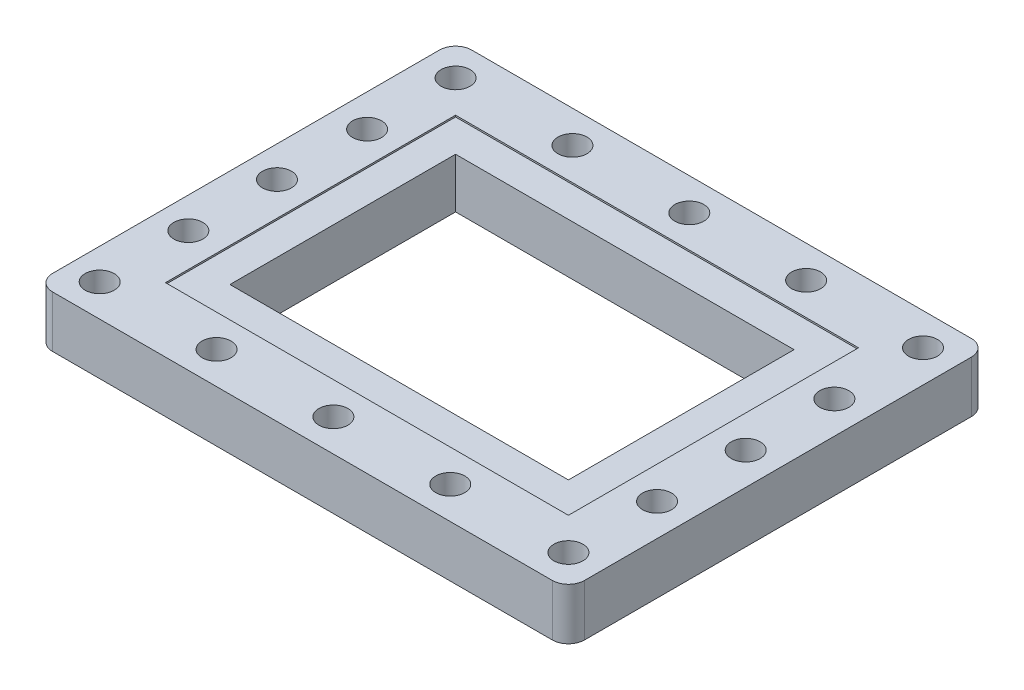
SolidWorks part; units mm, degrees
ref_plane "Front Plane" through (0, 0, 0) normal (0, 0, 1) x (1, 0, 0)
ref_plane "Top Plane" through (0, 0, 0) normal (0, 1, 0) x (1, 0, 0)
ref_plane "Right Plane" through (0, 0, 0) normal (1, 0, 0) x (0, 0, -1)
sketch "Sketch1" plane through (0, 0, 0) normal (0, 1, 0) x (1, 0, 0)
  line L1 (-14.684, 10.0891) -> (18.316, 10.0891)
  line L2 (-14.684, 10.0891) -> (-14.684, -15.9109)
  line L3 (-14.684, -15.9109) -> (18.316, -15.9109)
  line L4 (18.316, 10.0891) -> (18.316, -15.9109)
  dimension "D1" = 33
  dimension "D2" = 26
extrude "Boss-Extrude1" add sketch "Sketch1" along normal blind 3.1
sketch "Sketch2" plane through (0, 0, 15.9109) normal (0, 0, 1) x (1, 0, 0)
  line L0 (18.316, 3.1) -> (18.316, 0) construction
  line L1 (18.316, 2.1) -> (12.816, 2.1)
  line L2 (18.316, 2.1) -> (18.316, 1)
  line L3 (18.316, 1) -> (12.816, 1)
  line L4 (12.816, 2.1) -> (12.816, 1)
  line L5 (-14.684, 3.1) -> (18.316, 3.1) construction
  dimension "D1" = 5.5
  dimension "D2" = 1.1
  dimension "D3" = 1
extrude "Cut-Extrude1" [suppressed] cut sketch "Sketch2" against normal through all
sketch "Sketch3" plane through (0, 3.1, 0) normal (0, 1, 0) x (1, 0, 0)
  line L0 (-14.684, -15.9109) -> (18.316, -15.9109) construction
  line L1 (-14.684, 10.0891) -> (-10.684, 10.0891)
  line L2 (-14.684, 10.0891) -> (-14.684, -15.9109)
  line L3 (-14.684, -15.9109) -> (-10.684, -15.9109)
  line L4 (-10.684, 10.0891) -> (-10.684, -15.9109)
  line L5 (18.316, -15.9109) -> (18.316, 10.0891) construction
  line L6 (-10.684, 10.0891) -> (18.316, 10.0891)
  line L7 (-10.684, 10.0891) -> (-10.684, 6.0891)
  line L8 (-10.684, 6.0891) -> (18.316, 6.0891)
  line L9 (18.316, 10.0891) -> (18.316, 6.0891)
  line L11 (-10.684, -15.9109) -> (18.316, -15.9109)
  line L12 (-10.684, -15.9109) -> (-10.684, -11.9109)
  line L13 (-10.684, -11.9109) -> (18.316, -11.9109)
  line L14 (18.316, -15.9109) -> (18.316, -11.9109)
  line L15 (14.316, 6.0891) -> (18.316, 6.0891)
  line L16 (14.316, 6.0891) -> (14.316, -11.9109)
  line L17 (14.316, -11.9109) -> (18.316, -11.9109)
  line L18 (18.316, 6.0891) -> (18.316, -11.9109)
  line M7 (-14.684, 10.0891) -> (-14.684, -15.9109)
  line M8 (-14.684, -15.9109) -> (18.316, -15.9109)
  line M9 (18.316, -15.9109) -> (18.316, 10.0891)
  line M10 (18.316, 10.0891) -> (-14.684, 10.0891)
  dimension "D1" = 4
  dimension "D2" = 4
  dimension "D3" = 4
  dimension "D4" = 4
extrude "Boss-Extrude2" add sketch "Sketch3" along normal blind 0.1 contours L4 M10 M7 M8 | L4 L8 M9 M10 | L13 L4 M8 M9 | L16 L15 L18 L17
sketch "Sketch4" plane through (0, 0, 0) normal (0, -1, 0) x (1, 0, 0)
  line L0 (18.316, 15.9109) -> (18.316, -10.0891) construction
  line L1 (18.316, -10.0891) -> (-14.684, -10.0891) construction
  circle A0 centre (15.566, -5.3391) radius 0.5501
  circle A5 centre (15.566, 4.6609) radius 0.5501
  circle A6 centre (15.566, -0.3391) radius 0.5501
  circle A7 centre (10.7876, 6.1326) radius 0.5501
  dimension "D1" = 2.75
  dimension "D2" = 5
  dimension "D3" = 5
  dimension "D4" = 5
  dimension "D5" = 4.75
  dimension "D6" = 0
  dimension "D7" = 0
hole_wizard "Tap Drill for M2.5x0.45 Tap1" [suppressed] positions "Sketch5" profile "Sketch6" hole size "M2.5x0.45" standard "ANSI Metric"
sketch "Sketch5" plane through (0, 0, 0) normal (0, -1, 0) x (-1, 0, 0)
  point P0 (-3.066, 5.3391)
  point P3 (-3.066, 0.3391)
  point P6 (-3.066, -4.6609)
  point P9 (-3.0468, -9.6608)
sketch "Sketch6" plane through (3.066, 0, -5.3391) normal (1, 0, 0) x (0, 0, -1)
  line L0 (0, 0) -> (0, 1.675)
  line L1 (0, 1.675) -> (1.125, 0.999)
  line L2 (1.125, 0.999) -> (1.125, 0)
  line L5 (1.125, 0) -> (0, 0)
  line L10 (0, 1.675) -> (-1.125, 0.999) construction
  line L11 (0, -6.35) -> (0, 107.95) construction
  dimension "Hole Dia." = 2.25
  dimension "Hole Depth" = 0.999
  dimension "Drill Angle" = 118
sketch "Sketch7" plane through (0, 3.2, 0) normal (0, 1, 0) x (1, 0, 0)
  line L0 (-14.684, 10.0891) -> (-14.684, -15.9109) construction
  line L1 (18.316, -15.9109) -> (18.316, 10.0891) construction
  line L2 (18.316, 10.0891) -> (-14.684, 10.0891) construction
  circle A0 centre (-12.684, 8.0891) radius 0.882
  circle A1 centre (-12.7647, -13.9109) radius 0.882
  circle A2 centre (-12.6745, 2.5891) radius 0.882
  circle A3 centre (-12.7647, -2.9109) radius 0.882
  circle A4 centre (-12.7647, -8.4109) radius 0.882
  circle A5 centre (-5.434, 8.0891) radius 0.882
  circle A6 centre (1.816, 8.0891) radius 0.882
  circle A7 centre (1.7353, -13.9109) radius 0.882
  circle A9 centre (-5.5147, -13.9109) radius 0.882
  circle A10 centre (9.066, 8.0891) radius 0.882
  circle A11 centre (16.316, 8.0891) radius 0.882
  circle A12 centre (16.316, 2.5891) radius 0.882
  circle A13 centre (16.316, -2.9109) radius 0.882
  circle A14 centre (16.316, -8.4109) radius 0.882
  circle A15 centre (16.316, -13.9109) radius 0.882
  circle A16 centre (8.9853, -13.9109) radius 0.882
  dimension "D1" = 2
  dimension "D2" = 2
  dimension "D3" = 5.5
  dimension "D4" = 5.5
  dimension "D5" = 5.5
  dimension "D6" = 5.5
  dimension "D7" = 7.25
  dimension "D8" = 7.25
  dimension "D10" = 7.25
  dimension "D11" = 7.25
  dimension "D9" = 7.25
  dimension "D12" = 2
  dimension "D13" = 0
  dimension "D14" = 0
  dimension "D15" = 0
  dimension "D16" = 0
  dimension "D17" = 7.25
  dimension "D18" = 0
  dimension "D19" = 0
  dimension "D20" = 0
  dimension "D21" = 0
  dimension "D22" = 0
  dimension "D23" = 0
  dimension "D24" = 0
hole_wizard "Tap Drill for M2x0.4 Tap2" positions "Sketch8" profile "Sketch10" hole size "M2x0.4" standard "ANSI Metric" end condition through all
sketch "Sketch8" plane through (0, 3.2, 0) normal (0, 1, 0) x (1, 0, 0)
  point P0 (-12.684, 8.0891)
  point P4 (-12.6745, 2.5891)
  point P7 (-12.7647, -2.9109)
  point P10 (-12.7647, -8.4109)
  point P13 (-12.7647, -13.9109)
  point P16 (-5.434, 8.0891)
  point P19 (1.816, 8.0891)
  point P28 (1.7353, -13.9109)
  point P31 (-5.5147, -13.9109)
  point P34 (9.066, 8.0891)
  point P37 (16.316, 8.0891)
  point P40 (16.316, 2.5891)
  point P43 (16.316, -2.9109)
  point P46 (16.316, -8.4109)
  point P49 (16.316, -13.9109)
  point P52 (8.9853, -13.9109)
sketch "Sketch10" plane through (-12.684, 3.2, -8.0891) normal (1, 0, 0) x (0, 0, 1)
  line L0 (0, 0) -> (0, 3.2)
  line L1 (0, 3.2) -> (0.9, 3.2)
  line L2 (0.9, 3.2) -> (0.9, 0)
  line L5 (0.9, 0) -> (0, 0)
  line L11 (0, -6.35) -> (0, 107.95) construction
  dimension "Thru Hole Dia." = 1.8
  dimension "Thru Hole Depth" = 3.2
fillet "Fillet2" radius 1 4 edges at (-14.684, 1.6, 15.9109) (-14.684, 1.6, -10.0891) (18.316, 1.6, 15.9109) (18.316, 1.6, -10.0891)
sketch "Sketch11" plane through (0, 3.1, 0) normal (0, 1, 0) x (1, 0, 0)
  line L0 (-10.684, 6.0891) -> (-10.684, -11.9109) construction
  line L1 (-8.684, 4.0891) -> (12.316, 4.0891)
  line L2 (-8.684, 4.0891) -> (-8.684, -9.9109)
  line L3 (-8.684, -9.9109) -> (12.316, -9.9109)
  line L4 (12.316, 4.0891) -> (12.316, -9.9109)
  line L5 (-10.684, 6.0891) -> (14.316, 6.0891) construction
  line L6 (14.316, 6.0891) -> (14.316, -11.9109) construction
  line L7 (-10.684, -11.9109) -> (14.316, -11.9109) construction
  dimension "D1" = 2
  dimension "D2" = 2
  dimension "D3" = 2
  dimension "D4" = 2
extrude "Cut-Extrude2" cut sketch "Sketch11" against normal through all
equation "\"samplewidth\"= 25"
equation "\"D1@Sketch1\"=\"samplewidth\" + 8"
equation "\"sampleheight\"= 18"
equation "\"D2@Sketch1\"=\"sampleheight\" + 8"
equation "\"stickthickness\"=1.1"
equation "\"D1@Boss-Extrude1\"=\"stickthickness\"+2"
equation "\"stickwidth\"= 5.5"
equation "\"D1@Sketch2\"=\"stickwidth\""
equation "\"D2@Sketch2\"=\"stickthickness\""
equation "\"samplethickness\"=0.1"
equation "\"D1@Boss-Extrude2\"=\"samplethickness\""
equation "\"D1@Sketch4\"=\"stickwidth\"/2"
equation "\"dimtolerance\"= 0.5"
equation "\"D3@Sketch7\"=(\"sampleheight\" +4)/4"
equation "\"D4@Sketch7\"=(\"sampleheight\" +4)/4"
equation "\"D5@Sketch7\"=(\"sampleheight\" +4)/4"
equation "\"D6@Sketch7\"=(\"sampleheight\" +4)/4"
equation "\"D7@Sketch7\"=(\"samplewidth\" +4)/4"
equation "\"D8@Sketch7\"=(\"samplewidth\" +4)/4"
equation "\"D10@Sketch7\"=(\"samplewidth\" +4)/4"
equation "\"D11@Sketch7\"=(\"samplewidth\" +4)/4"
equation "\"D9@Sketch7\"=(\"samplewidth\" +4)/4"
equation "\"D17@Sketch7\"=(\"samplewidth\" +4)/4"
